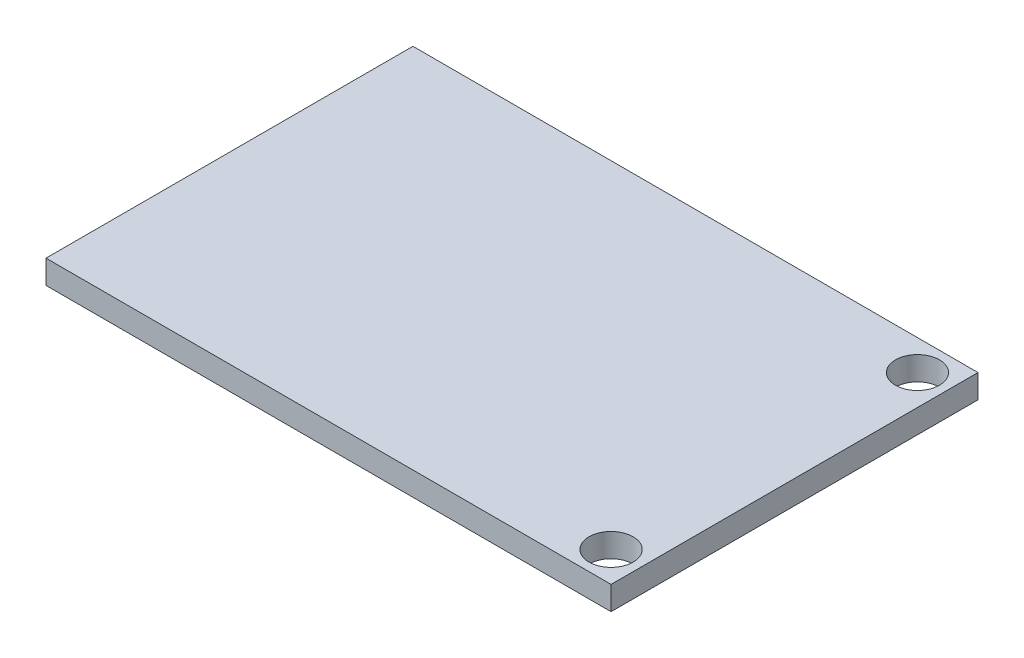
SolidWorks part; units mm, degrees
ref_plane "Front Plane" through (0, 0, 0) normal (0, 0, 1) x (1, 0, 0)
ref_plane "Top Plane" through (0, 0, 0) normal (0, 1, 0) x (1, 0, 0)
ref_plane "Right Plane" through (0, 0, 0) normal (1, 0, 0) x (0, 0, -1)
sketch "Sketch1" plane through (0, 0, 0) normal (0, 1, 0) x (1, 0, 0)
  line L1 (-19.558, -12.7) -> (19.558, -12.7)
  line L2 (-19.558, -12.7) -> (-19.558, 12.7)
  line L3 (-19.558, 12.7) -> (19.558, 12.7)
  line L4 (19.558, -12.7) -> (19.558, 12.7)
  line L5 (-19.558, -12.7) -> (19.558, 12.7) construction
  line L6 (-19.558, 12.7) -> (19.558, -12.7) construction
  point P0 (0, 0)
  dimension "D1" = 25.4
  dimension "D2" = 39.116
extrude "Boss-Extrude1" add sketch "Sketch1" along normal blind 1.6383
sketch "Sketch2" plane through (0, 1.6383, 0) normal (0, 1, 0) x (1, 0, 0)
  line L0 (0, 0) -> (29.1011, 0) construction
  line L1 (19.558, -12.7) -> (19.558, 12.7) construction
  line L2 (-19.558, -12.7) -> (19.558, -12.7) construction
  circle A0 centre (17.4625, -10.6045) radius 1.524
  circle A1 centre (17.4625, 10.6045) radius 1.524
  dimension "D1" = 3.048
  dimension "D3" = 2.0955
  dimension "D2" = 2.0955
extrude "Cut-Extrude1" cut sketch "Sketch2" against normal blind 1.6383
